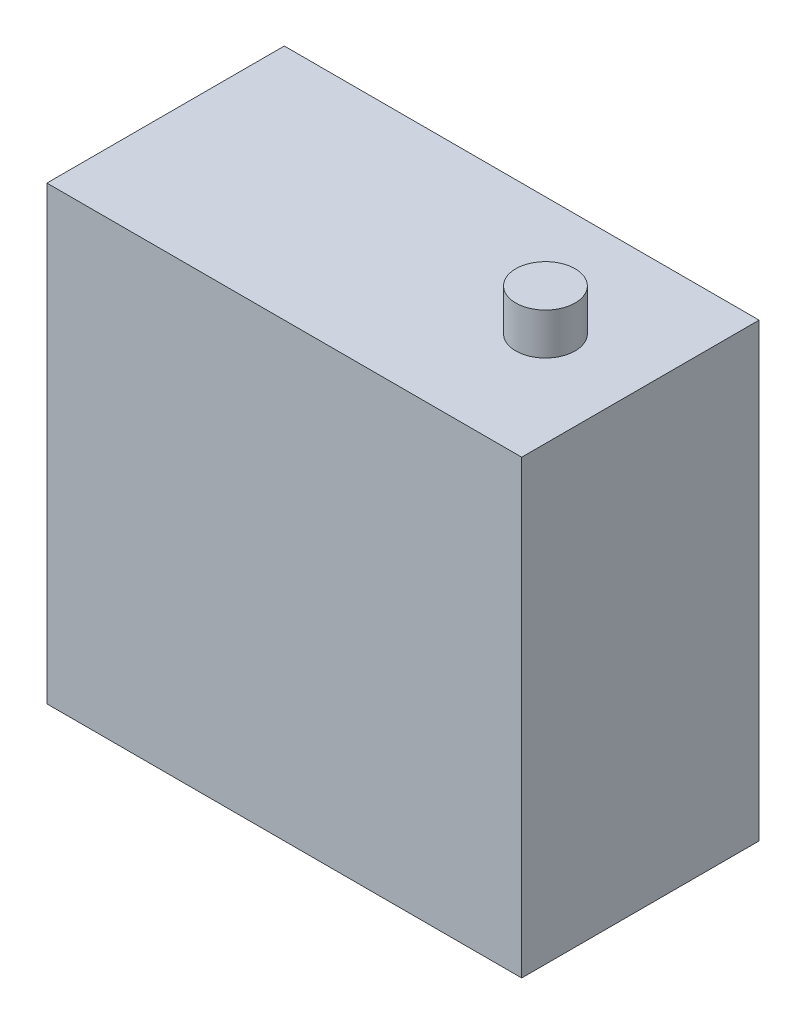
SolidWorks part; units mm, degrees
ref_plane "前视基准面" through (0, 0, 0) normal (0, 0, 1) x (1, 0, 0)
ref_plane "上视基准面" through (0, 0, 0) normal (0, 1, 0) x (1, 0, 0)
ref_plane "右视基准面" through (0, 0, 0) normal (1, 0, 0) x (0, 0, -1)
sketch "草图1" plane through (0, 0, 0) normal (0, 1, 0) x (1, 0, 0)
  line L1 (20, -10) -> (-20, -10)
  line L2 (20, -10) -> (20, 10)
  line L3 (20, 10) -> (-20, 10)
  line L4 (-20, -10) -> (-20, 10)
  line L5 (20, -10) -> (-20, 10) construction
  line L6 (20, 10) -> (-20, -10) construction
  point P0 (0, 0)
  dimension "D1" = 40
  dimension "D2" = 20
extrude "凸台-拉伸1" add sketch "草图1" along normal blind 38
sketch "草图2" plane through (0, 38, 0) normal (0, 1, 0) x (1, 0, 0)
  line L0 (0, 0) -> (20, 0) construction
  line L1 (20, -10) -> (20, 10) construction
  circle A0 centre (12, 0) radius 2.5
  dimension "D1" = 5
  dimension "D2" = 8
extrude "凸台-拉伸2" add sketch "草图2" along normal blind 3.5
